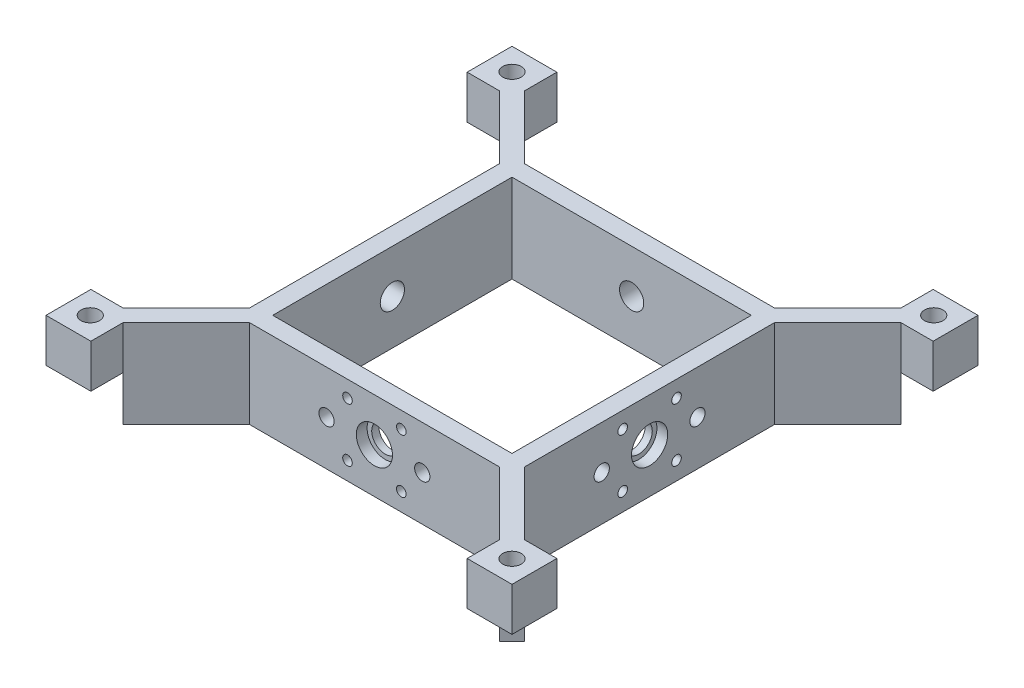
SolidWorks part; units mm, degrees
ref_plane "前视基准面" through (0, 0, 0) normal (0, 0, 1) x (1, 0, 0)
ref_plane "上视基准面" through (0, 0, 0) normal (0, 1, 0) x (1, 0, 0)
ref_plane "右视基准面" through (0, 0, 0) normal (1, 0, 0) x (0, 0, -1)
sketch "草图1" plane through (0, 0, 0) normal (0, 1, 0) x (1, 0, 0)
  line L0 (-77.9, 77.9) -> (-62.9, 77.9)
  line L5 (-46, -46) -> (46, -46) construction
  line L6 (-46, -46) -> (-46, 46) construction
  line L11 (-46, 46) -> (46, 46) construction
  line L12 (46, -46) -> (46, 46) construction
  line L13 (-46, -46) -> (46, 46) construction
  line L14 (-46, 46) -> (46, -46) construction
  line L15 (-40, -40) -> (40, -40)
  line L16 (-40, -40) -> (-40, 40)
  line L17 (-40, 40) -> (40, 40)
  line L18 (40, -40) -> (40, 40)
  line L19 (-40, -40) -> (40, 40) construction
  line L20 (-40, 40) -> (40, -40) construction
  line L21 (-77.9, -77.9) -> (77.9, -77.9) construction
  line L22 (-77.9, -77.9) -> (-77.9, 77.9) construction
  line L23 (-77.9, 77.9) -> (77.9, 77.9) construction
  line L24 (77.9, -77.9) -> (77.9, 77.9) construction
  line L25 (-77.9, -77.9) -> (77.9, 77.9) construction
  line L26 (-77.9, 77.9) -> (77.9, -77.9) construction
  line L27 (-62.9, 77.9) -> (-62.9, 62.9) construction
  line L28 (-62.9, 62.9) -> (-77.9, 62.9) construction
  line L29 (-77.9, 62.9) -> (-77.9, 77.9)
  line L30 (-62.9, 67.1426) -> (-67.1426, 62.9) construction
  line L31 (-77.9, 62.9) -> (-67.1426, 62.9)
  line L32 (-67.1426, 62.9) -> (-46, 41.7574)
  line L33 (-62.9, 77.9) -> (-62.9, 67.1426)
  line L34 (-62.9, 67.1426) -> (-41.7574, 46)
  line L35 (77.9, 77.9) -> (77.9, 62.9)
  line L36 (62.9, 77.9) -> (77.9, 77.9)
  line L37 (62.9, 77.9) -> (62.9, 67.1426)
  line L38 (77.9, 62.9) -> (67.1426, 62.9)
  line L39 (67.1426, 62.9) -> (46, 41.7574)
  line L40 (62.9, 67.1426) -> (41.7574, 46)
  line L41 (77.9, -77.9) -> (62.9, -77.9)
  line L42 (77.9, -62.9) -> (77.9, -77.9)
  line L43 (77.9, -62.9) -> (67.1426, -62.9)
  line L44 (62.9, -77.9) -> (62.9, -67.1426)
  line L45 (62.9, -67.1426) -> (41.7574, -46)
  line L46 (67.1426, -62.9) -> (46, -41.7574)
  line L47 (-77.9, -77.9) -> (-77.9, -62.9)
  line L48 (-62.9, -77.9) -> (-77.9, -77.9)
  line L49 (-62.9, -77.9) -> (-62.9, -67.1426)
  line L50 (-77.9, -62.9) -> (-67.1426, -62.9)
  line L51 (-67.1426, -62.9) -> (-46, -41.7574)
  line L52 (-62.9, -67.1426) -> (-41.7574, -46)
  line L53 (-41.7574, 46) -> (41.7574, 46)
  line L54 (46, 41.7574) -> (46, -41.7574)
  line L55 (41.7574, -46) -> (-41.7574, -46)
  line L56 (-46, -41.7574) -> (-46, 41.7574)
  point P0 (0, 0)
  point P6 (0, 0)
  point P11 (0, 0)
  point P47 (0, 0)
  dimension "D1" = 92
  dimension "D2" = 92
  dimension "D3" = 6
  dimension "D4" = 155.8
  dimension "D5" = 155.8
  dimension "D6" = 15
  dimension "D7" = 6
  dimension "D8" = 45
  dimension "D9" = 4
extrude "凸台-拉伸1" add sketch "草图1" along normal blind 30
sketch "草图2" plane through (0, 0, 0) normal (0, 1, 0) x (1, 0, 0)
  line L0 (-77.9, 77.9) -> (-62.9, 77.9)
  line L1 (-62.9, 77.9) -> (-62.9, 67.1426)
  line L2 (-62.9, 67.1426) -> (-67.1426, 62.9)
  line L3 (-67.1426, 62.9) -> (-77.9, 62.9)
  line L4 (-77.9, 62.9) -> (-77.9, 77.9)
  line L5 (62.9, 77.9) -> (77.9, 77.9)
  line L6 (77.9, 77.9) -> (77.9, 62.9)
  line L7 (77.9, 62.9) -> (67.1426, 62.9)
  line L8 (67.1426, 62.9) -> (62.9, 67.1426)
  line L9 (62.9, 67.1426) -> (62.9, 77.9)
  line L10 (77.9, -62.9) -> (77.9, -77.9)
  line L11 (77.9, -77.9) -> (62.9, -77.9)
  line L12 (62.9, -77.9) -> (62.9, -67.1426)
  line L13 (62.9, -67.1426) -> (67.1426, -62.9)
  line L14 (67.1426, -62.9) -> (77.9, -62.9)
  line L15 (-62.9, -77.9) -> (-77.9, -77.9)
  line L16 (-77.9, -77.9) -> (-77.9, -62.9)
  line L17 (-77.9, -62.9) -> (-67.1426, -62.9)
  line L18 (-67.1426, -62.9) -> (-62.9, -67.1426)
  line L19 (-62.9, -67.1426) -> (-62.9, -77.9)
  point P28 (0, 0)
  dimension "D1" = 4
extrude "切除-拉伸1" cut sketch "草图2" along normal blind 15
sketch "草图3" plane through (0, 30, 0) normal (0, 1, 0) x (1, 0, 0)
  line L3 (70.5, -70.5) -> (-70.5, -70.5) construction
  line L6 (70.5, -70.5) -> (70.5, 70.5) construction
  line L7 (70.5, 70.5) -> (-70.5, 70.5) construction
  line L8 (-70.5, -70.5) -> (-70.5, 70.5) construction
  line L9 (70.5, -70.5) -> (-70.5, 70.5) construction
  line L10 (70.5, 70.5) -> (-70.5, -70.5) construction
  circle A0 centre (-70.5, 70.5) radius 1.6
  point P0 (0, 0)
  point P1 (-70.5, 70.4)
  dimension "D1" = 3.2
  dimension "D2" = 141
extrude "切除-拉伸2" cut sketch "草图3" against normal through all
sketch "草图4" plane through (0, 30, 0) normal (0, 1, 0) x (1, 0, 0)
  circle A0 centre (-70.5, 70.5) radius 3.1
  dimension "D1" = 6.2
extrude "切除-拉伸3" cut sketch "草图4" against normal blind 5
sketch "草图5" plane through (0, 0, 0) normal (0, 0, 1) x (1, 0, 0)
  line L0 (0, 0) -> (0, 30) construction
  line L1 (-41.7574, 30) -> (41.7574, 30) construction
pattern_circular "阵列(圆周)1" count 4 over 360 about axis through (0, 0, 0) along (0, 1, 0) of "切除-拉伸2", "切除-拉伸3"
sketch "草图6" plane through (0, 0, 46) normal (0, 0, 1) x (1, 0, 0)
  line L0 (0, 30) -> (0, 0) construction
  line L1 (-41.7574, 0) -> (41.7574, 0) construction
  circle A0 centre (0, 15) radius 6.05
  point P7 (0, 0)
  point P8 (0, 15)
  dimension "D1" = 12.1
extrude "切除-拉伸4" cut sketch "草图6" against normal blind 3.6
sketch "草图7" plane through (0, 0, 42.4) normal (0, 0, 1) x (1, 0, 0)
  line L2 (0, 0) -> (0, 30) construction
  line L3 (0, 0) -> (0, 30) construction
  circle A0 centre (0, 15) radius 4.5
  point P2 (0, 15)
  dimension "D1" = 9
extrude "切除-拉伸5" cut sketch "草图7" against normal blind 2.5
sketch "草图8" plane through (0, 0, 46) normal (0, 0, 1) x (1, 0, 0)
  line L0 (0, 30) -> (0, 0) construction
  line L1 (0, 15) -> (-16, 15) construction
  line L3 (0, 0) -> (0, 30) construction
  circle A0 centre (-16, 15) radius 2.55
  circle A1 centre (16, 15) radius 2.55
  point P9 (0, 0)
  point P10 (0, 15)
  dimension "D2" = 5.1
  dimension "D1" = 16
extrude "切除-拉伸6" cut sketch "草图8" against normal blind 6
sketch "草图9" plane through (0, 0, 46) normal (0, 0, 1) x (1, 0, 0)
  line L1 (-9, 6) -> (9, 6) construction
  line L2 (-9, 6) -> (-9, 24) construction
  line L3 (-9, 24) -> (9, 24) construction
  line L4 (9, 6) -> (9, 24) construction
  line L5 (-9, 6) -> (9, 24) construction
  line L6 (-9, 24) -> (9, 6) construction
  line L9 (0, 0) -> (0, 30) construction
  circle A0 centre (9, 24) radius 1.6
  circle A1 centre (9, 6) radius 1.6
  circle A2 centre (-9, 6) radius 1.6
  circle A3 centre (-9, 24) radius 1.6
  point P0 (0, 15)
  point P5 (0, 15)
  point P11 (0, 0)
  point P13 (0, 15)
  dimension "D3" = 3.2
  dimension "D4" = 3.2
  dimension "D5" = 3.2
  dimension "D6" = 3.2
  dimension "D1" = 18
  dimension "D2" = 18
extrude "切除-拉伸7" cut sketch "草图9" against normal blind 6
pattern_circular "阵列(圆周)2" count 2 every 90 about axis through (0, 0, 0) along (0, 1, 0) of "切除-拉伸6", "切除-拉伸4", "切除-拉伸5", "切除-拉伸7"
sketch "草图10" plane through (-46, 0, 0) normal (-1, 0, 0) x (0, 0, 1)
  line L2 (0, 32) -> (0, 0) construction
  line L3 (0, 0) -> (0, 30) construction
  circle A0 centre (0, 15) radius 4.05
  point P2 (0, 14.5486)
  point P3 (0, 15)
  point P4 (0, 16)
  point P5 (0, 0)
  dimension "D1" = 8.1
extrude "切除-拉伸8" cut sketch "草图10" against normal blind 6
pattern_circular "阵列(圆周)3" count 2 every 90 about axis through (0, 0, 0) along (0, 1, 0) of "切除-拉伸8"
sketch "草图11" plane through (0, 30, 0) normal (0, 1, 0) x (1, 0, 0)
  line L28 (-77.9, 77.9) -> (-77.9, 62.9)
  line L29 (-77.9, 62.9) -> (-67.1426, 62.9)
  line L30 (-67.1426, 62.9) -> (-46, 41.7574)
  line L31 (-46, 41.7574) -> (-46, -41.7574)
  line L32 (-46, -41.7574) -> (-67.1426, -62.9)
  line L33 (-67.1426, -62.9) -> (-77.9, -62.9)
  line L34 (-77.9, -62.9) -> (-77.9, -77.9)
  line L35 (-77.9, -77.9) -> (-62.9, -77.9)
  line L36 (-62.9, -77.9) -> (-62.9, -67.1426)
  line L37 (-62.9, -67.1426) -> (-41.7574, -46)
  line L38 (-41.7574, -46) -> (41.7574, -46)
  line L39 (41.7574, -46) -> (62.9, -67.1426)
  line L40 (62.9, -67.1426) -> (62.9, -77.9)
  line L41 (62.9, -77.9) -> (77.9, -77.9)
  line L42 (77.9, -77.9) -> (77.9, -62.9)
  line L43 (77.9, -62.9) -> (67.1426, -62.9)
  line L44 (67.1426, -62.9) -> (46, -41.7574)
  line L45 (46, -41.7574) -> (46, 41.7574)
  line L46 (46, 41.7574) -> (67.1426, 62.9)
  line L47 (67.1426, 62.9) -> (77.9, 62.9)
  line L48 (77.9, 62.9) -> (77.9, 77.9)
  line L49 (77.9, 77.9) -> (62.9, 77.9)
  line L50 (62.9, 77.9) -> (62.9, 67.1426)
  line L51 (62.9, 67.1426) -> (41.7574, 46)
  line L52 (41.7574, 46) -> (-41.7574, 46)
  line L53 (-41.7574, 46) -> (-62.9, 67.1426)
  line L54 (-62.9, 67.1426) -> (-62.9, 77.9)
  line L55 (-62.9, 77.9) -> (-77.9, 77.9)
  line L56 (-77.9, 77.9) -> (-77.9, 62.9)
  line L57 (-77.9, 62.9) -> (-67.1426, 62.9)
  line L58 (-67.1426, 62.9) -> (-46, 41.7574)
  line L59 (-46, 41.7574) -> (-46, -41.7574)
  line L60 (-46, -41.7574) -> (-67.1426, -62.9)
  line L61 (-67.1426, -62.9) -> (-77.9, -62.9)
  line L62 (-77.9, -62.9) -> (-77.9, -77.9)
  line L63 (-77.9, -77.9) -> (-62.9, -77.9)
  line L64 (-62.9, -77.9) -> (-62.9, -67.1426)
  line L65 (-62.9, -67.1426) -> (-41.7574, -46)
  line L66 (-41.7574, -46) -> (41.7574, -46)
  line L67 (41.7574, -46) -> (62.9, -67.1426)
  line L68 (62.9, -67.1426) -> (62.9, -77.9)
  line L69 (62.9, -77.9) -> (77.9, -77.9)
  line L70 (77.9, -77.9) -> (77.9, -62.9)
  line L71 (77.9, -62.9) -> (67.1426, -62.9)
  line L72 (67.1426, -62.9) -> (46, -41.7574)
  line L73 (46, -41.7574) -> (46, 41.7574)
  line L74 (46, 41.7574) -> (67.1426, 62.9)
  line L75 (67.1426, 62.9) -> (77.9, 62.9)
  line L76 (77.9, 62.9) -> (77.9, 77.9)
  line L77 (77.9, 77.9) -> (62.9, 77.9)
  line L78 (62.9, 77.9) -> (62.9, 67.1426)
  line L79 (62.9, 67.1426) -> (41.7574, 46)
  line L80 (41.7574, 46) -> (-41.7574, 46)
  line L81 (-41.7574, 46) -> (-62.9, 67.1426)
  line L82 (-62.9, 67.1426) -> (-62.9, 77.9)
  line L83 (-62.9, 77.9) -> (-77.9, 77.9)
  dimension "D1" = 0
extrude "切除-拉伸9" cut sketch "草图11" against normal blind 0.5
